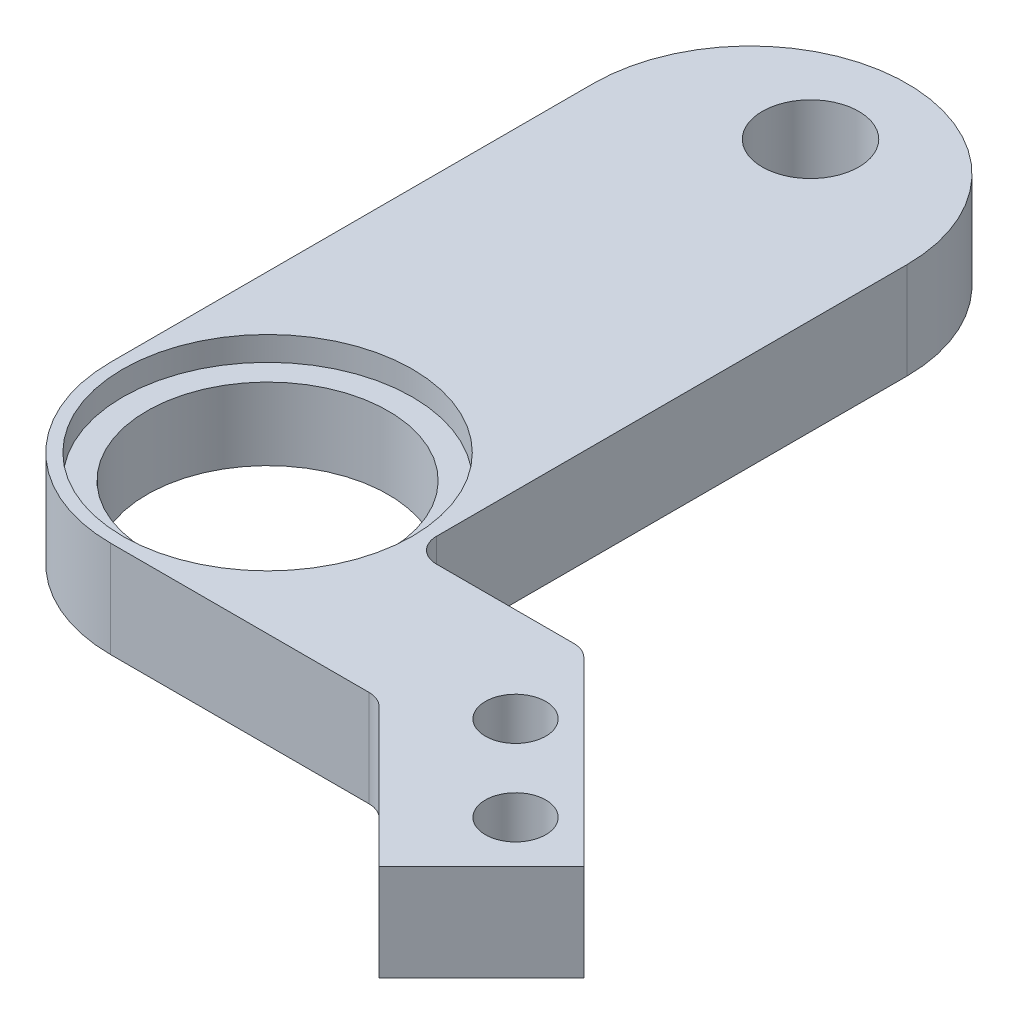
SolidWorks part; units mm, degrees
material "6061 Alloy"
ref_plane "Front Plane" through (0, 0, 0) normal (0, 0, 1) x (1, 0, 0)
ref_plane "Top Plane" through (0, 0, 0) normal (0, 1, 0) x (1, 0, 0)
ref_plane "Right Plane" through (0, 0, 0) normal (1, 0, 0) x (0, 0, -1)
ref_plane "Plane1" through (0, -2, 0) normal (0, -1, 0) x (1, 0, 0)
sketch "Sketch1" plane through (0, -2, 0) normal (0, -1, 0) x (1, 0, 0)
  line L0 (11.12, 26.5) -> (-6.5, 26.5)
  line L1 (-6.5, 26.5) -> (-6.5, 0)
  line L2 (6.5, 0) -> (6.5, 20.5)
  line L3 (6.5, 20.5) -> (13.6053, 20.5)
  line L4 (13.6053, 20.5) -> (13.6053, 36.1006)
  line L5 (13.6053, 36.1006) -> (11.12, 38.5859)
  line L6 (11.12, 38.5859) -> (11.12, 26.5)
  arc A0 (-6.5, 0) -> (6.5, 0) centre (0, 0) ccw
  dimension "D1" = 17.62
extrude "Boss-Extrude1" add sketch "Sketch1" against normal blind 4
draft "Draft1" type of draft neutral plane draft angle 45 faces to draft 1 face at (13.6053, 0, 28.3003) neutral plane through (6.5, 2, 20.5) neutral plane normal (0, 0, -1) parameters "D1"=45
draft "Draft2" type of draft neutral plane draft angle 45 faces to draft 1 face at (11.12, 0, 32.5429) neutral plane through (11.12, 2, 26.5) neutral plane normal (0, 0, 1) parameters "D1"=45
ref_plane "Plane2" through (0, 0, 20) normal (0, 0, 1) x (1, 0, 0)
sketch "Sketch2" plane through (0, 0, 20) normal (0, 0, 1) x (1, 0, 0)
  line L0 (0, 0.7952) -> (0, 2)
  line L1 (0, 0.7952) -> (0, -2)
  line L2 (0, -2) -> (5, -2)
  line L3 (5, -0.7952) -> (5, -2)
  line L5 (5, -0.7952) -> (5, 1)
  line L6 (11.12, 2) -> (-6.5, 2) construction
  line L7 (0, 2) -> (6, 2)
  line L8 (0, 0.7952) -> (0, -2) construction
  line L9 (6, 2) -> (6, 1)
  line L10 (6, 1) -> (5, 1)
  dimension "D1" = 1
  dimension "D2" = 1
hole_wizard "Ø4.0 (4) Diameter Hole1" positions "Sketch4" profile "Sketch3" hole size "Ø4.0" standard "ANSI Metric" end condition through all
sketch "Sketch4" plane through (0, 2, 0) normal (0, 1, 0) x (1, 0, 0)
  point P0 (0, 2.5)
sketch "Sketch3" plane through (0, 2, -2.5) normal (1, 0, 0) x (0, 0, 1)
  line L0 (0, 0) -> (0, 4)
  line L1 (0, 4) -> (2, 4)
  line L2 (2, 4) -> (2, 0)
  line L5 (2, 0) -> (0, 0)
  line L11 (0, -6.35) -> (0, 107.95) construction
  dimension "Thru Hole Dia." = 4
  dimension "Thru Hole Depth" = 4
hole_wizard "CSK for M3 SFHCS1" positions "Sketch6" profile "Sketch5" countersink size "M3" standard "ANSI Metric" end condition through all
sketch "Sketch6" plane through (0, -2, 0) normal (0, -1, 0) x (-1, 0, 0)
  line L0 (-13.6053, -20.5) -> (-21.4056, -28.3003) construction
  point P0 (-14.6902, -24.4134)
  point P1 (-18.2258, -27.9489)
  dimension "D1" = 2
  dimension "D2" = 2
sketch "Sketch5" plane through (14.6902, -2, 24.4134) normal (1, 0, 0) x (0, 0, -1)
  line L0 (0, 0) -> (0, 4)
  line L1 (0, 4) -> (1.25, 4)
  line L2 (1.25, 4) -> (1.25, 0.75)
  line L3 (1.25, 0.75) -> (2, 0)
  line L5 (2, 0) -> (0, 0)
  line L6 (-1.25, 0.75) -> (-2, 0) construction
  line L11 (0, -6.35) -> (0, 107.95) construction
  dimension "Thru Hole Dia." = 2.5
  dimension "Thru Hole Depth" = 4
  dimension "Near C'Sink Dia." = 4
  dimension "Near C'Sink Angle" = 90
fillet "Fillet1" radius 1 3 edges at (6.5, 0, 20.5) (11.12, 0, 26.5) (13.6053, 0, 20.5)
fillet "Fillet2" radius 6.5 1 edges at (-6.5, 0, 26.5)
hole_wizard "Hole2" positions "3DSketch2" profile "Sketch8" legacy end condition through all
sketch3d "3DSketch2"
  line L0 (0, 2, 20) -> (0, -2, 20) construction
  point P0 (0, 2, 20)
sketch "Sketch8" plane through (0, 2, 20) normal (1, 0, 0) x (0, 0, 1)
  line L0 (0, 0) -> (0, 4)
  line L1 (0, 4) -> (5, 4)
  line L2 (5, 4) -> (5, 1)
  line L3 (5, 1) -> (6, 1)
  line L4 (6, 1) -> (6, 0)
  line L5 (6, 0) -> (0, 0)
  line L6 (0, 110) -> (0, -10) construction
  dimension "Diameter" = 10
  dimension "Depth" = 4
  dimension "C-Bore Diameter" = 12
  dimension "C-Bore Depth" = 1
